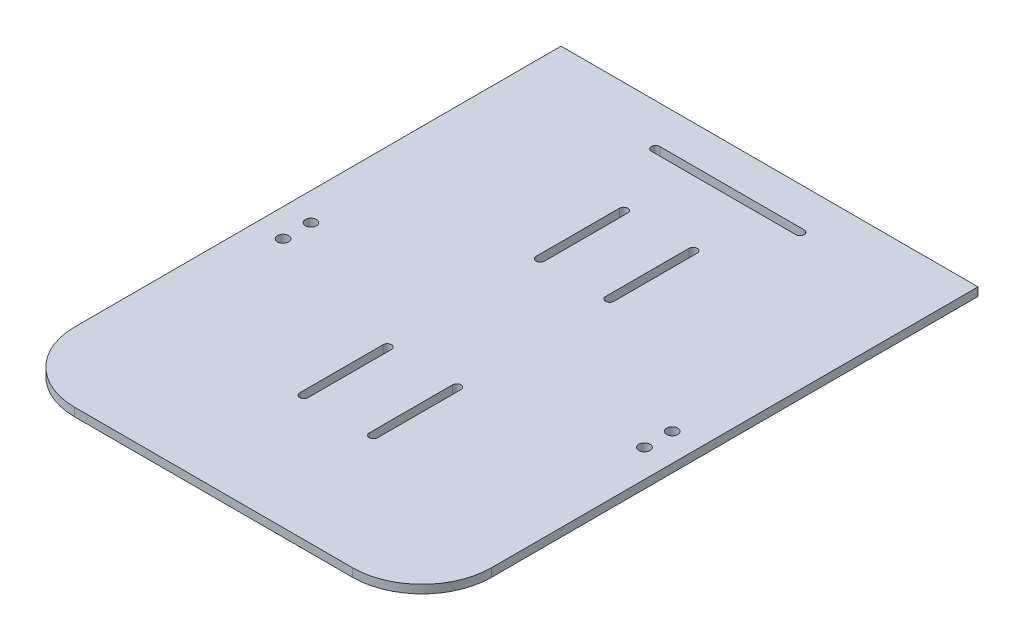
SolidWorks part; units mm, degrees
ref_plane "Front Plane" through (0, 0, 0) normal (0, 0, 1) x (1, 0, 0)
ref_plane "Top Plane" through (0, 0, 0) normal (0, 1, 0) x (1, 0, 0)
ref_plane "Right Plane" through (0, 0, 0) normal (1, 0, 0) x (0, 0, -1)
sketch "Sketch1" plane through (0, 0, 0) normal (0, 1, 0) x (1, 0, 0)
  line L0 (-25.9779, 185) -> (25.9779, 185) construction
  line L1 (-50, 0) -> (50, 0)
  line L2 (0, 0) -> (0, 200) construction
  line L3 (-75, 200) -> (75, 200)
  line L4 (75, 25) -> (75, 200)
  line L5 (-25.9779, 186.5) -> (25.9779, 186.5)
  line L6 (75, 180) -> (75, 115)
  line L7 (-25.9779, 183.5) -> (25.9779, 183.5)
  line L11 (12.5, 160) -> (12.5, 130) construction
  line L12 (14, 160) -> (14, 130)
  line L13 (11, 160) -> (11, 130)
  line L14 (12.5, 75) -> (12.5, 45) construction
  line L15 (14, 75) -> (14, 45)
  line L16 (11, 75) -> (11, 45)
  line L19 (-75, 180) -> (-75, 115)
  line L21 (-75, 25) -> (-75, 200)
  line L22 (-12.5, 75) -> (-12.5, 45) construction
  line L23 (-14, 75) -> (-14, 45)
  line L24 (-11, 75) -> (-11, 45)
  line L25 (-12.5, 160) -> (-12.5, 130) construction
  line L26 (-14, 160) -> (-14, 130)
  line L27 (-11, 160) -> (-11, 130)
  arc A0 (-25.9779, 186.5) -> (-25.9779, 183.5) centre (-25.9779, 185) ccw
  arc A1 (25.9779, 183.5) -> (25.9779, 186.5) centre (25.9779, 185) ccw
  circle A2 centre (65, 100) radius 2
  circle A3 centre (65, 90) radius 2
  arc A4 (14, 160) -> (11, 160) centre (12.5, 160) ccw
  arc A5 (11, 130) -> (14, 130) centre (12.5, 130) ccw
  arc A6 (50, 0) -> (75, 25) centre (50, 25) ccw
  arc A7 (14, 75) -> (11, 75) centre (12.5, 75) ccw
  arc A8 (11, 45) -> (14, 45) centre (12.5, 45) ccw
  arc A9 (-50, 0) -> (-75, 25) centre (-50, 25) cw
  circle A10 centre (-65, 90) radius 2
  circle A11 centre (-65, 100) radius 2
  arc A12 (-14, 75) -> (-11, 75) centre (-12.5, 75) cw
  arc A13 (-11, 45) -> (-14, 45) centre (-12.5, 45) cw
  arc A14 (-14, 160) -> (-11, 160) centre (-12.5, 160) cw
  arc A15 (-11, 130) -> (-14, 130) centre (-12.5, 130) cw
  point P9 (0, 185)
  point P22 (12.5, 145)
  point P29 (75, 0)
  point P32 (12.5, 60)
  point P51 (-12.5, 60)
  point P56 (-75, 0)
  point P59 (-12.5, 145)
  dimension "D11" = 4
  dimension "D14" = 4
  dimension "D19" = 25
  dimension "D23" = 1.5
  dimension "D1" = 75
  dimension "D2" = 200
  dimension "D3" = 62.5
  dimension "D4" = 3
  dimension "D5" = 15
  dimension "D6" = 75
  dimension "D10" = 100
  dimension "D12" = 10
  dimension "D13" = 10
  dimension "D15" = 3
  dimension "D16" = 30
  dimension "D18" = 55
  dimension "D20" = 3
  dimension "D21" = 30
  dimension "D22" = 12.5
  dimension "D24" = 60
extrude "Boss-Extrude1" add sketch "Sketch1" along normal blind 3
sketch "Sketch2" plane through (0, 3, 0) normal (0, 1, 0) x (1, 0, 0)
  line L0 (-75, 25) -> (-75, 200) construction
  line L2 (-50, 0) -> (50, 0) construction
  line L4 (-75, 200) -> (75, 200) construction
  line L5 (-75, 25) -> (-75, 200) construction
  line L6 (75, 25) -> (75, 200) construction
  circle A0 centre (-55, 20) radius 3
  circle A1 centre (55, 20) radius 3
  circle A2 centre (-55, 160) radius 3
  circle A3 centre (55, 160) radius 3
  dimension "D5" = 6
  dimension "D6" = 6
  dimension "D7" = 6
  dimension "D10" = 6
  dimension "D1" = 20
  dimension "D2" = 20
  dimension "D3" = 110
  dimension "D4" = 20
  dimension "D8" = 20
  dimension "D9" = 40
  dimension "D11" = 20
  dimension "D12" = 40
